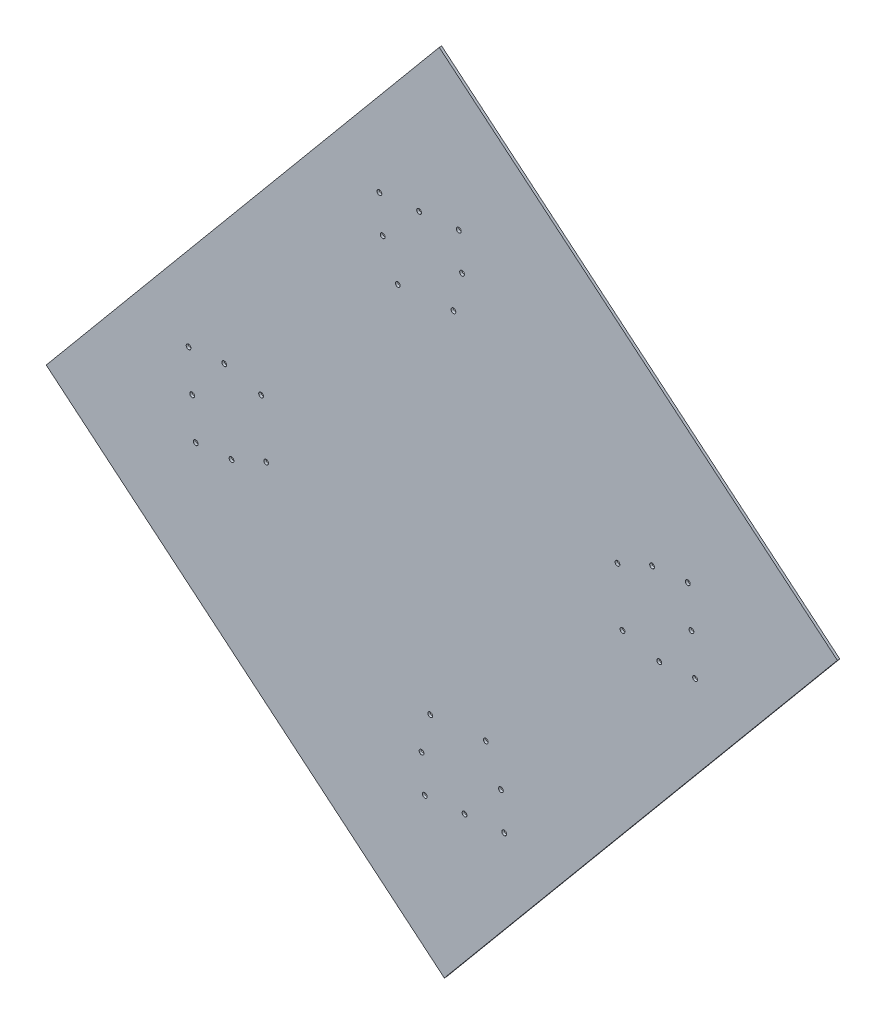
SolidWorks part; units mm, degrees
ref_plane "Front Plane" through (0, 0, 0) normal (0, 0, 1) x (1, 0, 0)
ref_plane "Top Plane" through (0, 0, 0) normal (0, 1, 0) x (1, 0, 0)
ref_plane "Right Plane" through (0, 0, 0) normal (1, 0, 0) x (0, 0, -1)
sketch "Sketch1" plane through (0, 0, 0) normal (0, 0, 1) x (1, 0, 0)
  line L4 (1018.0531, -2273.2638) -> (1511.0081, -1681.7442)
  line L5 (1511.0081, -1681.7442) -> (1011.6733, -1265.6134)
  line L6 (1011.6733, -1265.6134) -> (518.7184, -1857.133)
  line L7 (518.7184, -1857.133) -> (1018.0531, -2273.2638)
  line L8 (1018.0531, -2273.2638) -> (1511.0081, -1681.7442)
  line L9 (1511.0081, -1681.7442) -> (1011.6733, -1265.6134)
  line L10 (1011.6733, -1265.6134) -> (518.7184, -1857.133)
  line L11 (518.7184, -1857.133) -> (1018.0531, -2273.2638)
  circle A1 centre (701.7538, -1797.8962) radius 3
  circle A2 centre (701.7538, -1797.8962) radius 3
  circle A3 centre (1327.9727, -1740.981) radius 3
  circle A4 centre (1327.9727, -1740.981) radius 3
  circle A5 centre (1235.1741, -1714.2709) radius 3
  circle A6 centre (1235.1741, -1714.2709) radius 3
  circle A7 centre (1278.6317, -1695.2594) radius 3
  circle A8 centre (1278.6317, -1695.2594) radius 3
  circle A9 centre (1323.447, -1691.1863) radius 3
  circle A10 centre (1323.447, -1691.1863) radius 3
  circle A11 centre (697.2281, -1748.1014) radius 3
  circle A12 centre (697.2281, -1748.1014) radius 3
  circle A13 centre (788.2164, -1754.8936) radius 3
  circle A14 centre (788.2164, -1754.8936) radius 3
  circle A15 centre (742.0434, -1744.0283) radius 3
  circle A16 centre (742.0434, -1744.0283) radius 3
  circle A17 centre (751.0948, -1843.6178) radius 3
  circle A18 centre (751.0948, -1843.6178) radius 3
  circle A19 centre (794.5523, -1824.6063) radius 3
  circle A20 centre (794.5523, -1824.6063) radius 3
  circle A21 centre (706.2795, -1847.6909) radius 3
  circle A22 centre (706.2795, -1847.6909) radius 3
  circle A23 centre (1241.5101, -1783.9836) radius 3
  circle A24 centre (1241.5101, -1783.9836) radius 3
  circle A25 centre (1332.4984, -1790.7758) radius 3
  circle A26 centre (1332.4984, -1790.7758) radius 3
  circle A27 centre (1287.6831, -1794.8489) radius 3
  circle A28 centre (1287.6831, -1794.8489) radius 3
  circle A29 centre (940.684, -1505.6701) radius 3
  circle A30 centre (940.684, -1505.6701) radius 3
  circle A31 centre (936.6109, -1460.8549) radius 3
  circle A32 centre (936.6109, -1460.8549) radius 3
  circle A33 centre (986.4057, -1456.3292) radius 3
  circle A34 centre (986.4057, -1456.3292) radius 3
  circle A35 centre (1036.2004, -1451.8035) radius 3
  circle A36 centre (1036.2004, -1451.8035) radius 3
  circle A37 centre (1040.2735, -1496.6187) radius 3
  circle A38 centre (1040.2735, -1496.6187) radius 3
  circle A39 centre (1029.4082, -1542.7917) radius 3
  circle A40 centre (1029.4082, -1542.7917) radius 3
  circle A41 centre (959.6956, -1549.1277) radius 3
  circle A42 centre (959.6956, -1549.1277) radius 3
  circle A43 centre (1089.0424, -2033.2071) radius 3
  circle A44 centre (1089.0424, -2033.2071) radius 3
  circle A45 centre (1093.1156, -2078.0224) radius 3
  circle A46 centre (1093.1156, -2078.0224) radius 3
  circle A47 centre (1043.3208, -2082.548) radius 3
  circle A48 centre (1043.3208, -2082.548) radius 3
  circle A49 centre (993.5261, -2087.0737) radius 3
  circle A50 centre (993.5261, -2087.0737) radius 3
  circle A51 centre (989.4529, -2042.2585) radius 3
  circle A52 centre (989.4529, -2042.2585) radius 3
  circle A53 centre (1000.3182, -1996.0855) radius 3
  circle A54 centre (1000.3182, -1996.0855) radius 3
  circle A55 centre (1070.0309, -1989.7495) radius 3
  circle A56 centre (1070.0309, -1989.7495) radius 3
  dimension "D1" = 0
  dimension "D2" = 0
  dimension "D3" = 0
  dimension "D4" = 0
  dimension "D5" = 0
  dimension "D6" = 0
  dimension "D7" = 0
  dimension "D8" = 0
  dimension "D9" = 0
  dimension "D10" = 0
  dimension "D11" = 0
  dimension "D12" = 0
  dimension "D13" = 0
  dimension "D14" = 0
  dimension "D15" = 0
  dimension "D16" = 0
  dimension "D17" = 0
  dimension "D18" = 0
  dimension "D19" = 0
  dimension "D20" = 0
  dimension "D21" = 0
  dimension "D22" = 0
  dimension "D23" = 0
  dimension "D24" = 0
  dimension "D25" = 0
  dimension "D26" = 0
  dimension "D27" = 0
  dimension "D28" = 0
  dimension "D29" = 0
extrude "Boss-Extrude1" add sketch "Sketch1" along normal blind 3
